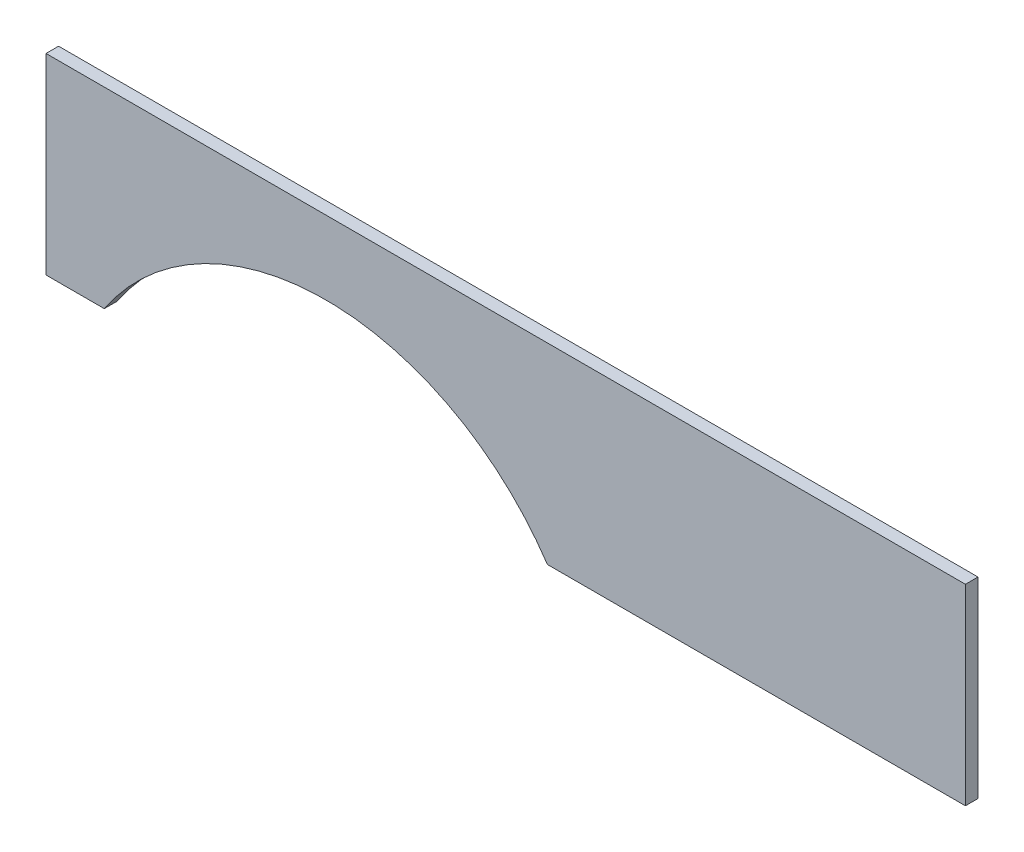
SolidWorks part; units mm, degrees
ref_plane "Front Plane" through (0, 0, 0) normal (0, 0, 1) x (1, 0, 0)
ref_plane "Top Plane" through (0, 0, 0) normal (0, 1, 0) x (1, 0, 0)
ref_plane "Right Plane" through (0, 0, 0) normal (1, 0, 0) x (0, 0, -1)
sketch "Sketch1" plane through (0, 0, 0) normal (0, 0, 1) x (1, 0, 0)
  line L1 (0, 0) -> (219.075, 0)
  line L2 (0, 0) -> (0, 45.72)
  line L3 (0, 45.72) -> (219.075, 45.72)
  line L4 (219.075, 0) -> (219.075, 45.72)
  dimension "D1" = 219.075
  dimension "D2" = 45.72
extrude "Boss-Extrude1" add sketch "Sketch1" along normal blind 3
sketch "Sketch2" plane through (0, 0, 3) normal (0, 0, 1) x (1, 0, 0)
  line L0 (0, 45.72) -> (0, 0) construction
  line L2 (0, 0) -> (219.075, 0) construction
  circle A0 centre (66.68, -35.29) radius 63.5
  dimension "D1" = 127
  dimension "D2" = 66.68
  dimension "D3" = 35.29
extrude "Cut-Extrude1" cut sketch "Sketch2" against normal through all both and the other way through all
